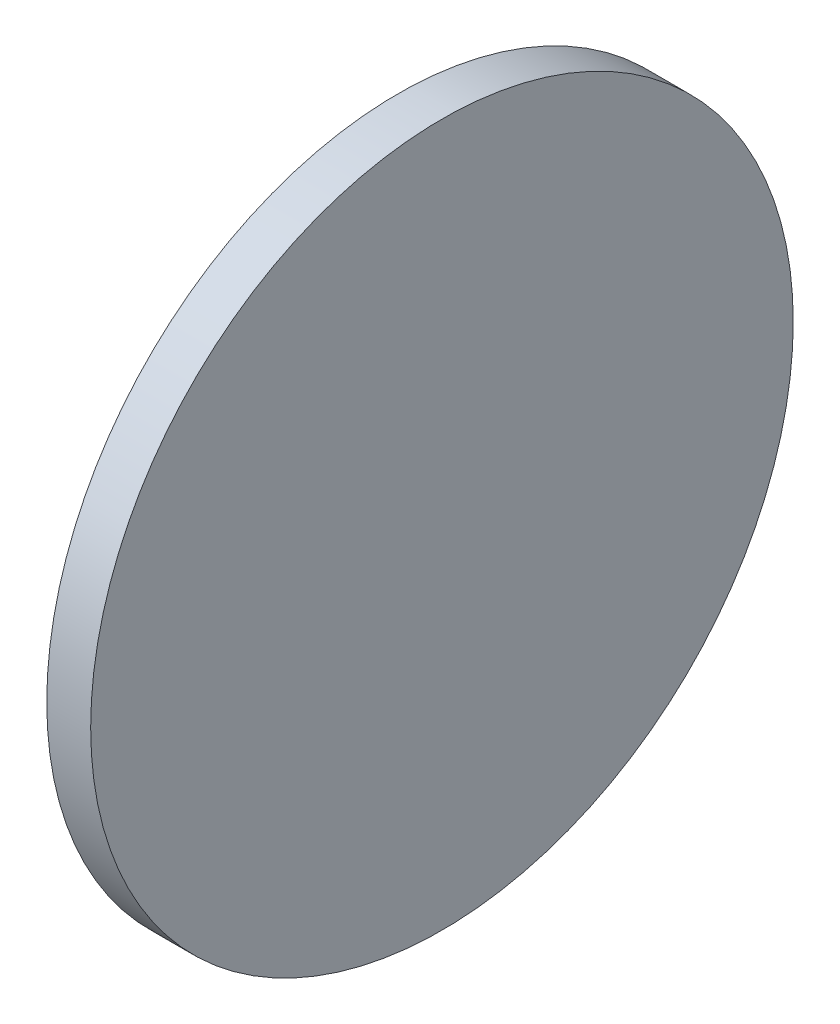
SolidWorks part; units mm, degrees
material "1060 Alloy"
ref_plane "Front Plane" through (0, 0, 0) normal (0, 0, 1) x (1, 0, 0)
ref_plane "Top Plane" through (0, 0, 0) normal (0, 1, 0) x (1, 0, 0)
ref_plane "Right Plane" through (0, 0, 0) normal (1, 0, 0) x (0, 0, -1)
sketch "Axial profile (mm)" plane through (0, 0, 0) normal (0, 0, 1) x (1, 0, 0)
  line L0 (-110, 0) -> (75, 0) construction
  line L1 (168.7, 0) -> (171.875, 0)
  line L2 (171.875, 0) -> (171.875, 25.4)
  line L3 (171.875, 25.4) -> (168.7, 25.4)
  line L4 (168.7, 25.4) -> (168.7, 0)
revolve "Full revolution" add sketch "Axial profile (mm)" angle 360 about L0
